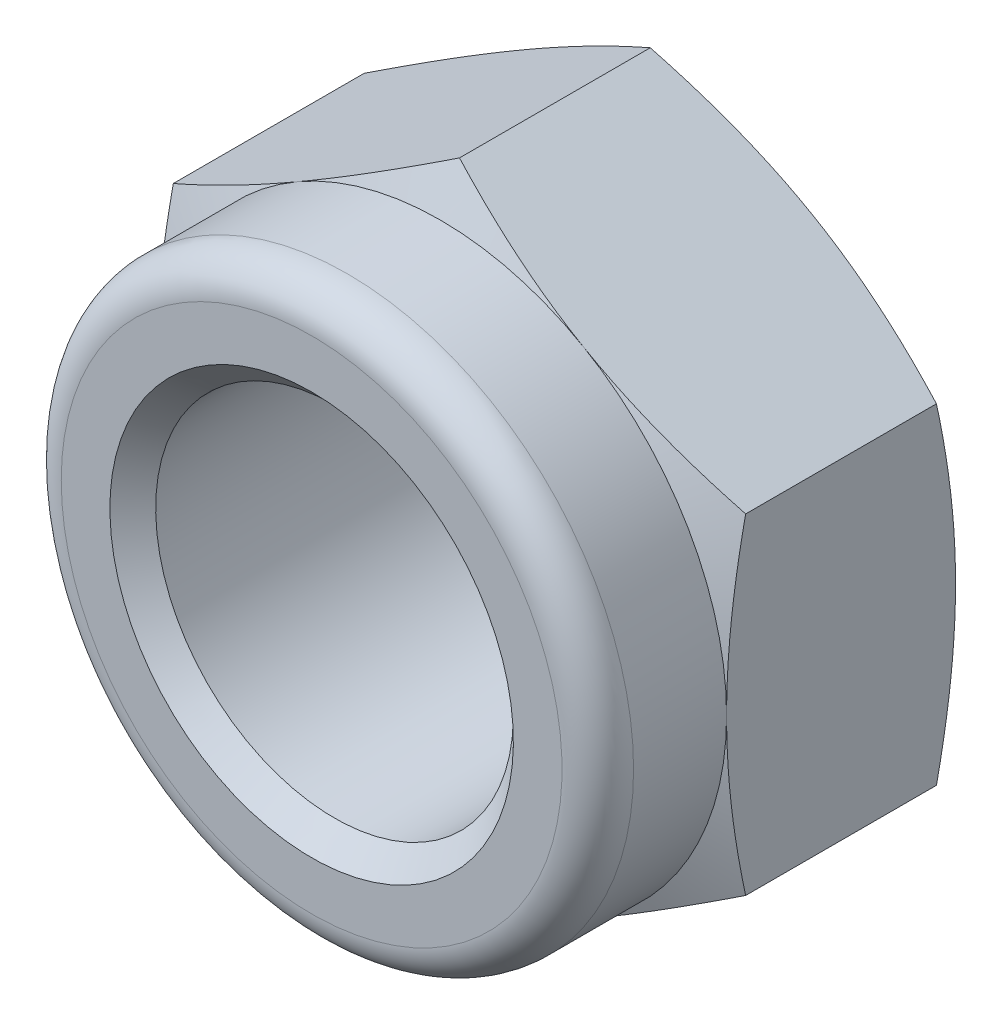
SolidWorks part; units mm, degrees
material "Plain Carbon Steel"
ref_plane "Front Plane" through (0, 0, 0) normal (0, 0, 1) x (1, 0, 0)
ref_plane "Top Plane" through (0, 0, 0) normal (0, 1, 0) x (1, 0, 0)
ref_plane "Right Plane" through (0, 0, 0) normal (1, 0, 0) x (0, 0, -1)
sketch "Sketch1" plane through (0, 0, 0) normal (0, 0, 1) x (1, 0, 0)
  line L1 (0, -4.6188) -> (4, -2.3094)
  line L2 (4, -2.3094) -> (4, 2.3094)
  line L3 (4, 2.3094) -> (0, 4.6188)
  line L4 (0, 4.6188) -> (-4, 2.3094)
  line L5 (-4, 2.3094) -> (-4, -2.3094)
  line L6 (-4, -2.3094) -> (0, -4.6188)
  circle A0 centre (0, 0) radius 4 construction
  circle A1 centre (0, 0) radius 2.5
  dimension "D2" = 5
  dimension "D1" = 8
extrude "Boss-Extrude1" add sketch "Sketch1" along normal blind 3.2
sketch "Sketch3" plane through (0, 0, 0) normal (0, 1, 0) x (0, 0, -1)
  line L0 (-3.2, 4) -> (-4.5, 4)
  line L1 (-3.2, -4) -> (-3.2, 0) construction
  line L2 (-5, 3.5) -> (-5, 2.5)
  line L3 (-5, 2.5) -> (-3.2, 2.5)
  line L5 (-3.2, 2.5) -> (-3.2, 4)
  line L6 (0, 0) -> (-2.4, 0) construction
  arc A0 (-4.5, 4) -> (-5, 3.5) centre (-4.5, 3.5) ccw
  dimension "D1" = 0.5
  dimension "D2" = 5
revolve "Revolve1" add sketch "Sketch3" angle 360 about L6
sketch "Sketch2" plane through (0, 0, 0) normal (1, 0, 0) x (0, 0, -1)
  line L0 (-3.2, 4.6188) -> (-3.2, 4)
  line L1 (-3.2, 2.3094) -> (-3.2, 3.4641) construction
  line L2 (-3.2, 4) -> (-2.9333, 4.6188)
  line L3 (-3.2, 4.6188) -> (0, 4.6188) construction
  line L4 (-2.9333, 4.6188) -> (-3.2, 4.6188)
  line L5 (-0.2667, 4.6188) -> (0, 4.6188)
  line L6 (0, 4.6188) -> (0, 4)
  line L7 (0, 2.3094) -> (0, 4.6188) construction
  line L8 (0, 4) -> (-0.2667, 4.6188)
  line L9 (-2.9333, 4.6188) -> (-2.6667, 4.6188) construction
  line L10 (-2.6667, 4.6188) -> (-2.4, 4.6188) construction
  line L11 (-2.4, 4.6188) -> (-2.1333, 4.6188) construction
  line L12 (-2.1333, 4.6188) -> (-1.8667, 4.6188) construction
  line L13 (-1.8667, 4.6188) -> (-1.6, 4.6188) construction
  line L14 (-1.6, 4.6188) -> (-1.3333, 4.6188) construction
  line L15 (-1.3333, 4.6188) -> (-1.0667, 4.6188) construction
  line L16 (-1.0667, 4.6188) -> (-0.8, 4.6188) construction
  line L17 (-0.8, 4.6188) -> (-0.5333, 4.6188) construction
  line L18 (0, 0) -> (-2.4, 0) construction
  line L20 (-5, 2.5) -> (-4.68, 2.5)
  line L21 (-4.68, 2.5) -> (-5, 2.82)
  line L22 (-5, 2.82) -> (-5, 2.5)
  line L23 (0, 2.5) -> (-0.32, 2.5)
  line L24 (0, -2.3094) -> (0, 2.3094) construction
  line L25 (-0.32, 2.5) -> (0, 2.82)
  line L26 (0, 2.82) -> (0, 2.5)
  line L27 (-5, 3.5) -> (-5, -3.5) construction
  line L28 (-2.56, 2.5) -> (-2.88, 2.5) construction
  line L29 (-2.88, 2.5) -> (-3.2, 2.5) construction
  line L30 (-2.56, 2.5) -> (-2.24, 2.5) construction
  line L31 (-2.24, 2.5) -> (-1.92, 2.5) construction
  line L32 (-1.92, 2.5) -> (-1.6, 2.5) construction
  line L33 (-1.6, 2.5) -> (-1.28, 2.5) construction
  line L34 (-1.28, 2.5) -> (-0.96, 2.5) construction
  line L35 (-0.96, 2.5) -> (-0.64, 2.5) construction
  line L36 (-0.64, 2.5) -> (-0.32, 2.5) construction
  line L37 (-0.5333, 4.6188) -> (-0.2667, 4.6188) construction
  line L38 (-3.2, 0) -> (-3.2, 2.3094) construction
  dimension "D1" = 8
revolve "Cut-Revolve1" cut sketch "Sketch2" angle 360 about L18
